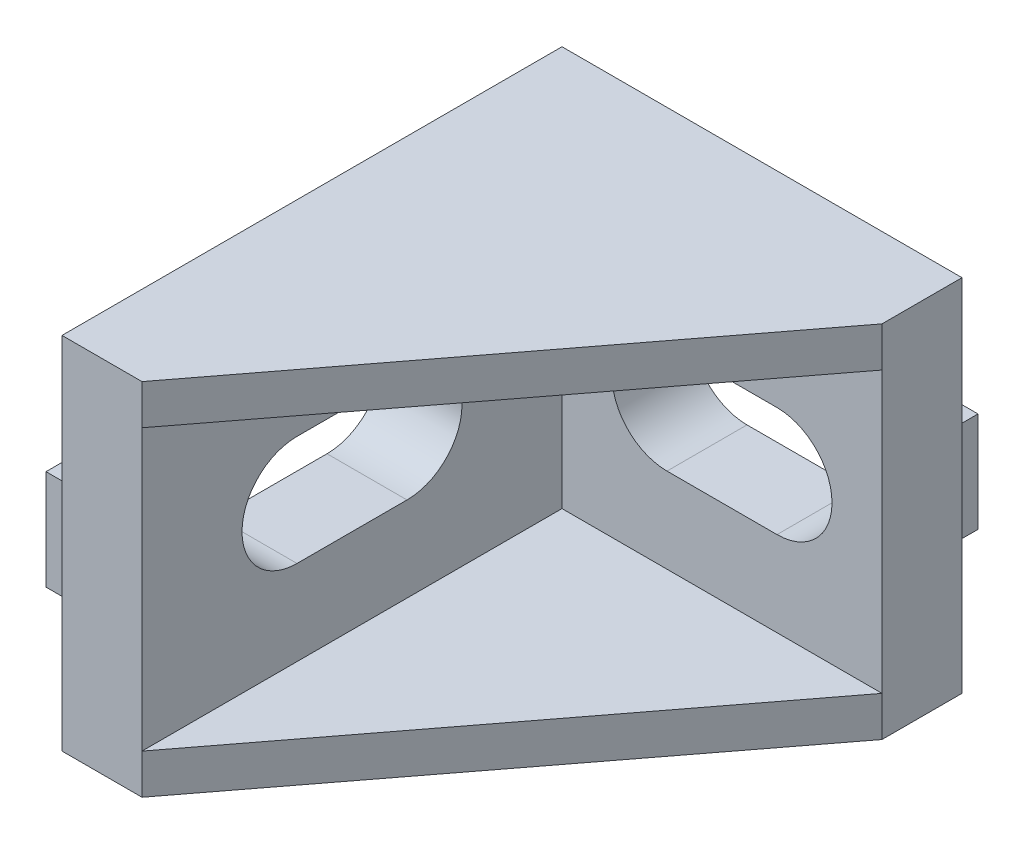
SolidWorks part; units mm, degrees
ref_plane "정면" through (0, 0, 0) normal (0, 0, 1) x (1, 0, 0)
ref_plane "윗면" through (0, 0, 0) normal (0, 1, 0) x (1, 0, 0)
ref_plane "우측면" through (0, 0, 0) normal (1, 0, 0) x (0, 0, -1)
sketch "스케치1" plane through (0, 0, 0) normal (0, 0, 1) x (1, 0, 0)
  line L1 (-10, 9) -> (10, 9)
  line L2 (-10, 9) -> (-10, -9)
  line L3 (-10, -9) -> (10, -9)
  line L4 (10, 9) -> (10, -9)
  line L5 (-10, 9) -> (10, -9) construction
  line L6 (-10, -9) -> (10, 9) construction
  point P0 (0, 0)
  dimension "D1" = 20
  dimension "D2" = 18
extrude "보스-돌출1" add sketch "스케치1" along normal blind 25
sketch "스케치2" plane through (0, 0, 25) normal (0, 0, 1) x (1, 0, 0)
  line L0 (10, -9) -> (10, 9) construction
  line L1 (10, 7) -> (-6, 7)
  line L2 (10, 7) -> (10, -7)
  line L3 (10, -7) -> (-6, -7)
  line L4 (-6, 7) -> (-6, -7)
  line L5 (-10, 9) -> (-10, -9) construction
  line L6 (10, 9) -> (-10, 9) construction
  line L7 (-10, -9) -> (10, -9) construction
  point P10 (0, 9)
  dimension "D1" = 4
  dimension "D2" = 2
  dimension "D3" = 2
extrude "컷-돌출1" cut sketch "스케치2" against normal blind 21
sketch "스케치4" plane through (0, -7, 0) normal (0, 1, 0) x (1, 0, 0)
  line L0 (-6, -25) -> (10, -4)
  line L1 (10, -4) -> (10, -25)
  line L2 (10, -25) -> (-6, -25)
extrude "컷-돌출2" cut sketch "스케치4" against normal through all both and the other way through all
sketch "스케치5" plane through (0, 0, 4) normal (0, 0, 1) x (1, 0, 0)
  line L0 (-0.75, 0) -> (4.75, 0) construction
  line L1 (-0.75, 2.75) -> (4.75, 2.75)
  line L2 (-0.75, -2.75) -> (4.75, -2.75)
  line L3 (10, -7) -> (10, 7) construction
  arc A0 (-0.75, 2.75) -> (-0.75, -2.75) centre (-0.75, 0) ccw
  arc A1 (4.75, -2.75) -> (4.75, 2.75) centre (4.75, 0) ccw
  point P3 (2, 0)
  dimension "D2" = 2.75
  dimension "D1" = 5.5
  dimension "D3" = 8
extrude "컷-돌출3" cut sketch "스케치5" against normal through all both
sketch "스케치6" plane through (-6, 0, 0) normal (1, 0, 0) x (0, 0, -1)
  line L0 (-17.25, 0) -> (-11.75, 0) construction
  line L1 (-17.25, 2.75) -> (-11.75, 2.75)
  line L2 (-17.25, -2.75) -> (-11.75, -2.75)
  line L3 (-4, -7) -> (-25, -7) construction
  line L4 (-25, 7) -> (-25, -7) construction
  arc A0 (-17.25, 2.75) -> (-17.25, -2.75) centre (-17.25, 0) ccw
  arc A1 (-11.75, -2.75) -> (-11.75, 2.75) centre (-11.75, 0) ccw
  point P2 (-14.5, 0)
  dimension "D2" = 2.75
  dimension "D1" = 5.5
  dimension "D3" = 7
  dimension "D4" = 10.5
extrude "컷-돌출4" cut sketch "스케치6" against normal through all both
sketch "스케치7" plane through (0, 0, 0) normal (0, 0, -1) x (-1, 0, 0)
  line L1 (-9.8, 2.5) -> (-7.8, 2.5)
  line L2 (-9.8, 2.5) -> (-9.8, -2.5)
  line L3 (-9.8, -2.5) -> (-7.8, -2.5)
  line L4 (-7.8, 2.5) -> (-7.8, -2.5)
  line L5 (-10, -9) -> (-10, 9) construction
  line L6 (-10, 9) -> (10, 9) construction
  line L7 (10, 9) -> (10, -9) construction
  line L8 (9.8, 2.5) -> (7.8, 2.5)
  line L9 (9.8, 2.5) -> (9.8, -2.5)
  line L10 (9.8, -2.5) -> (7.8, -2.5)
  line L11 (7.8, 2.5) -> (7.8, -2.5)
  line L12 (10, -9) -> (-10, -9) construction
  point P6 (-9.8, 0)
  point P15 (9.8, 0)
  dimension "D1" = 2.2
  dimension "D2" = 5
  dimension "D3" = 9
  dimension "D4" = 2
  dimension "D5" = 5
  dimension "D6" = 2.2
  dimension "D7" = 2
  dimension "D8" = 9
extrude "보스-돌출2" add sketch "스케치7" along normal blind 1
sketch "스케치8" plane through (-10, 0, 0) normal (-1, 0, 0) x (0, 0, 1)
  line L0 (0, 9) -> (0, -9) construction
  line L1 (0.2, 2.5) -> (2.2, 2.5)
  line L2 (0.2, 2.5) -> (0.2, -2.5)
  line L3 (0.2, -2.5) -> (2.2, -2.5)
  line L4 (2.2, 2.5) -> (2.2, -2.5)
  line L5 (22.8, 2.5) -> (24.8, 2.5)
  line L6 (22.8, 2.5) -> (22.8, -2.5)
  line L7 (22.8, -2.5) -> (24.8, -2.5)
  line L8 (24.8, 2.5) -> (24.8, -2.5)
  line L9 (25, 9) -> (25, -9) construction
  line L10 (25, -9) -> (0, -9) construction
  point P12 (0.2, 0)
  point P14 (24.8, 0)
  dimension "D1" = 2.2
  dimension "D2" = 2
  dimension "D3" = 2
  dimension "D4" = 2.2
  dimension "D5" = 5
  dimension "D6" = 5
  dimension "D7" = 9
  dimension "9" = 9
extrude "보스-돌출3" add sketch "스케치8" along normal blind 1
